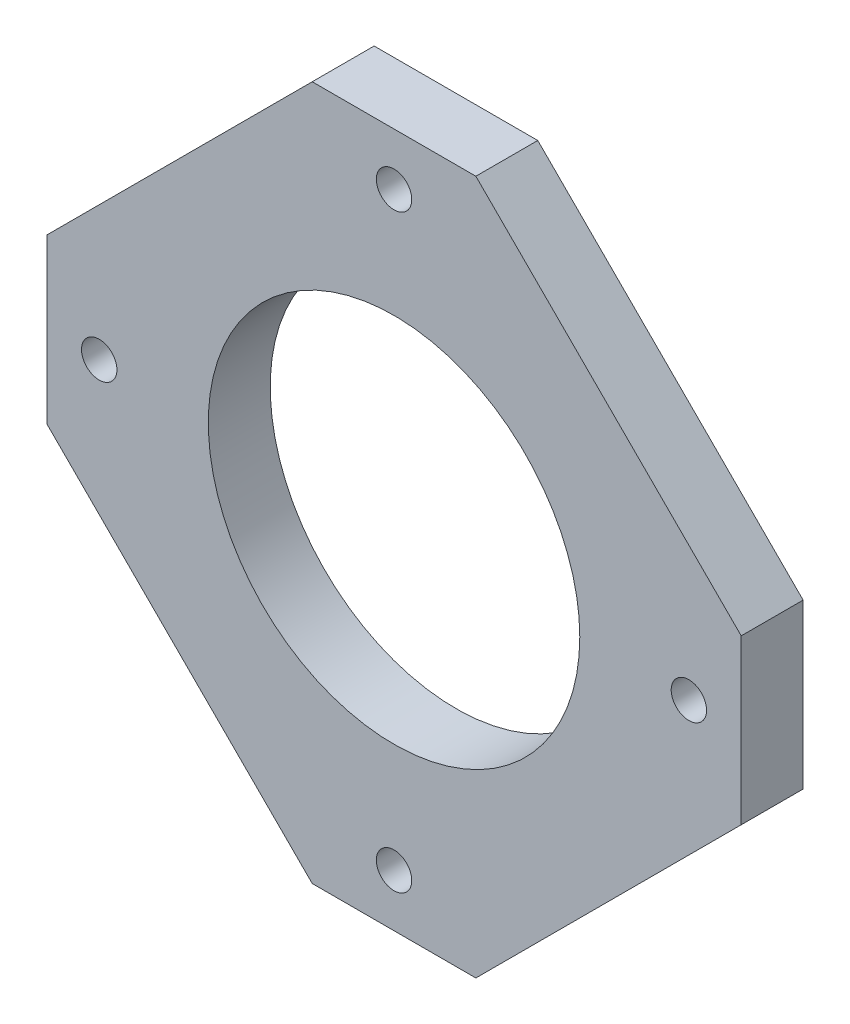
SolidWorks part; units mm, degrees
material "ABS"
ref_plane "Front Plane" through (0, 0, 0) normal (0, 0, 1) x (1, 0, 0)
ref_plane "Top Plane" through (0, 0, 0) normal (0, 1, 0) x (1, 0, 0)
ref_plane "Right Plane" through (0, 0, 0) normal (1, 0, 0) x (0, 0, -1)
sketch "Sketch1" plane through (0, 0, 0) normal (0, 0, 1) x (1, 0, 0)
  line L1 (-39.25, -39.25) -> (39.25, -39.25)
  line L2 (-39.25, -39.25) -> (-39.25, 39.25)
  line L3 (-39.25, 39.25) -> (39.25, 39.25)
  line L4 (39.25, -39.25) -> (39.25, 39.25)
  line L5 (-39.25, -39.25) -> (39.25, 39.25) construction
  line L6 (-39.25, 39.25) -> (39.25, -39.25) construction
  point P0 (0, 0)
  dimension "D1" = 78.5
extrude "Boss-Extrude1" add sketch "Sketch1" along normal mid plane 7
sketch "Sketch3" plane through (0, 0, 3.5) normal (0, 0, 1) x (1, 0, 0)
  circle A0 centre (0, 0) radius 21
  dimension "D1" = 42
extrude "Cut-Extrude2" cut sketch "Sketch3" against normal through all
sketch "Sketch4" plane through (0, 0, 3.5) normal (0, 0, 1) x (1, 0, 0)
  line L0 (0, 0) -> (0, 21) construction
  line L1 (0, -33.333) -> (33.333, 0) construction
  line L2 (0, -33.333) -> (-33.333, 0) construction
  line L3 (-33.333, 0) -> (0, 33.333) construction
  line L4 (33.333, 0) -> (0, 33.333) construction
  line L5 (0, -33.333) -> (0, 33.333) construction
  line L6 (-33.333, 0) -> (33.333, 0) construction
  circle A0 centre (0, 33.333) radius 2
  circle A1 centre (-33.333, 0) radius 2
  circle A2 centre (0, -33.333) radius 2
  circle A3 centre (33.333, 0) radius 2
  circle A4 centre (0, 0) radius 21 construction
  point P0 (0, 0)
  dimension "D2" = 4
  dimension "D1" = 47.14
extrude "Cut-Extrude3" cut sketch "Sketch4" against normal through all
chamfer "Chamfer1" distance 30 angle 45 4 edges at (-39.25, -39.25, 0) (39.25, -39.25, 0) (39.25, 39.25, 0) (-39.25, 39.25, 0)
